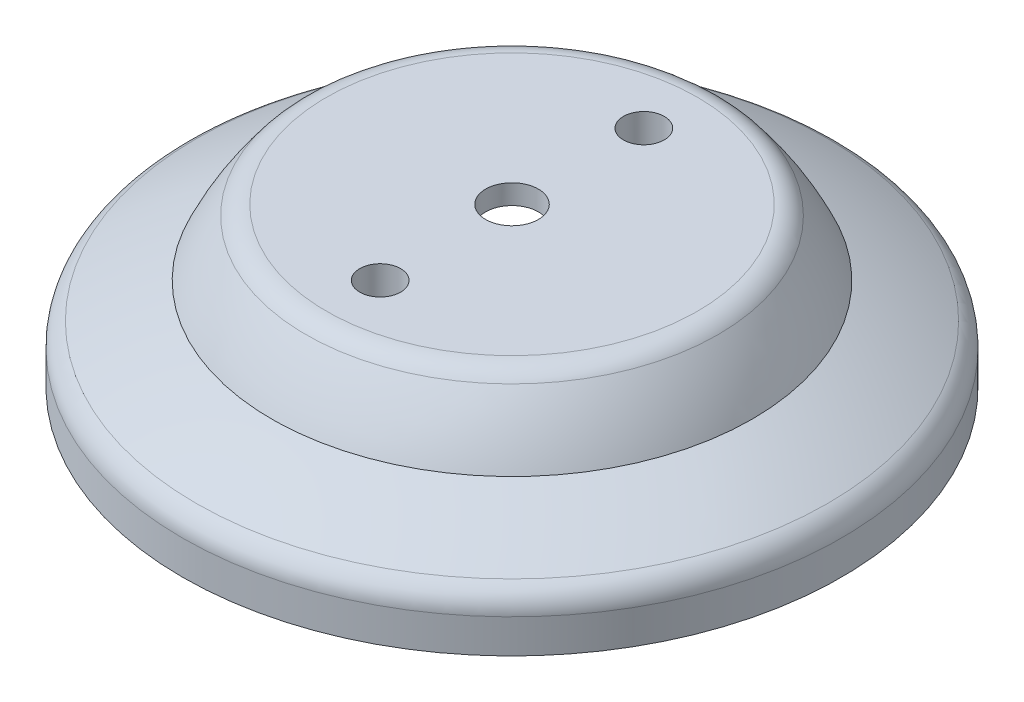
SolidWorks part; units mm, degrees
ref_plane "Alzado" through (0, 0, 0) normal (0, 0, 1) x (1, 0, 0)
ref_plane "Planta" through (0, 0, 0) normal (0, 1, 0) x (1, 0, 0)
ref_plane "Vista lateral" through (0, 0, 0) normal (1, 0, 0) x (0, 0, -1)
sketch "Croquis3" plane through (0, 0, 0) normal (0, 0, 1) x (1, 0, 0)
  line L0 (0, 0) -> (0, 12) construction
  line L1 (0, 12) -> (15, 12)
  line L2 (0, 0) -> (0, 12)
  line L3 (18.2288, 7) -> (0, 7) construction
  line L4 (0, 0) -> (25, 0)
  line L5 (25, 0) -> (25, 3.7426)
  arc A0 (18.2288, 7) -> (15, 12) centre (0, -1.2288) ccw
  arc A1 (25, 3.7426) -> (18.2288, 7) centre (0, -39.5587) ccw
  dimension "D3" = 40
  dimension "D4" = 100
  dimension "D1" = 12
  dimension "D2" = 15
  dimension "D6" = 5
  dimension "D7" = 25
revolve "Revolución1" add sketch "Croquis3" angle 360 about L2
sketch "Croquis4" plane through (0, 0, 0) normal (0, 0, 1) x (1, 0, 0)
  line L0 (0, 1.5) -> (0, 10.5)
  line L2 (0, 10.5) -> (0, 12) construction
  line L3 (15, 12) -> (-15, 12) construction
  line L8 (14.3069, 10.5) -> (-14.3069, 10.5)
  line L9 (-23.5, 1.5) -> (23.5, 1.5)
  line L10 (14.3069, 10.5) -> (0, 10.5)
  line L11 (0, 1.5) -> (23.5, 1.5)
  line L12 (-23.5, 2.8677) -> (-23.5, 1.5)
  line L14 (23.5, 1.5) -> (23.5, 2.8677)
  line L15 (23.5, 1.5) -> (23.5, 2.8677)
  arc A8 (-17.1021, 5.826) -> (-23.5, 2.8677) centre (0, -39.5587) ccw
  arc A9 (-14.3069, 10.5) -> (-17.1021, 5.826) centre (0, -1.2288) ccw
  arc A10 (23.5, 2.8677) -> (17.1021, 5.826) centre (0, -39.5587) ccw
  arc A11 (17.1021, 5.826) -> (14.3069, 10.5) centre (0, -1.2288) ccw
  arc A14 (23.5, 2.8677) -> (17.1021, 5.826) centre (0, -39.5587) ccw
  arc A15 (17.1021, 5.826) -> (14.3069, 10.5) centre (0, -1.2288) ccw
  dimension "D1" = 1.5
revolve "Cortar-Revolución1" cut sketch "Croquis4" angle 360 about L2
sketch "Croquis5" plane through (0, 12, 0) normal (0, 1, 0) x (1, 0, 0)
  circle A0 centre (0, 0) radius 2
  dimension "D1" = 4
extrude "Cortar-Extruir1" cut sketch "Croquis5" against normal blind 6
sketch "Croquis6" plane through (0, 0, 0) normal (0, -1, 0) x (1, 0, 0)
  circle A1 centre (0, 0) radius 23.5 construction
  circle A2 centre (0, 0) radius 23.5
extrude "Cortar-Extruir2" cut sketch "Croquis6" against normal blind 0.5
sketch "Croquis7" plane through (0, 10.5, 0) normal (0, -1, 0) x (1, 0, 0)
  line L0 (0, 0) -> (0, 14.3069) construction
  line L1 (-14.3069, 0) -> (14.3069, 0) construction
  circle A0 centre (0, 0) radius 14.3069 construction
  circle A1 centre (0, 10) radius 1.55
  circle A2 centre (0, 10) radius 3.05
  circle A3 centre (0, -10) radius 1.55
  circle A4 centre (0, -10) radius 3.05
  dimension "D1" = 3.1
  dimension "D3" = 1.5
  dimension "D2" = 10
extrude "Saliente-Extruir1" add sketch "Croquis7" along normal offset from surface (9.5 mm away) 1 up to face at (0, 0, -23.5)
sketch "Croquis8" plane through (0, 10.5, 0) normal (0, -1, 0) x (1, 0, 0)
  circle A0 centre (0, -10) radius 1.55 construction
  circle A1 centre (0, 10) radius 1.55 construction
  circle A2 centre (0, -10) radius 1.55
  circle A3 centre (0, 10) radius 1.55
extrude "Cortar-Extruir3" cut sketch "Croquis8" against normal blind 5.5
fillet "Redondeo1" radius 2 1 edges at (0, 12, -15)
fillet "Redondeo2" radius 2 1 edges at (0, 3.7426, -25)
sketch "Croquis9" plane through (0, 0.5, 0) normal (0, -1, 0) x (1, 0, 0)
  circle A0 centre (0, 0) radius 23.5 construction
  circle A1 centre (0, 0) radius 23.5
extrude "Cortar-Extruir4" cut sketch "Croquis9" against normal blind 1
